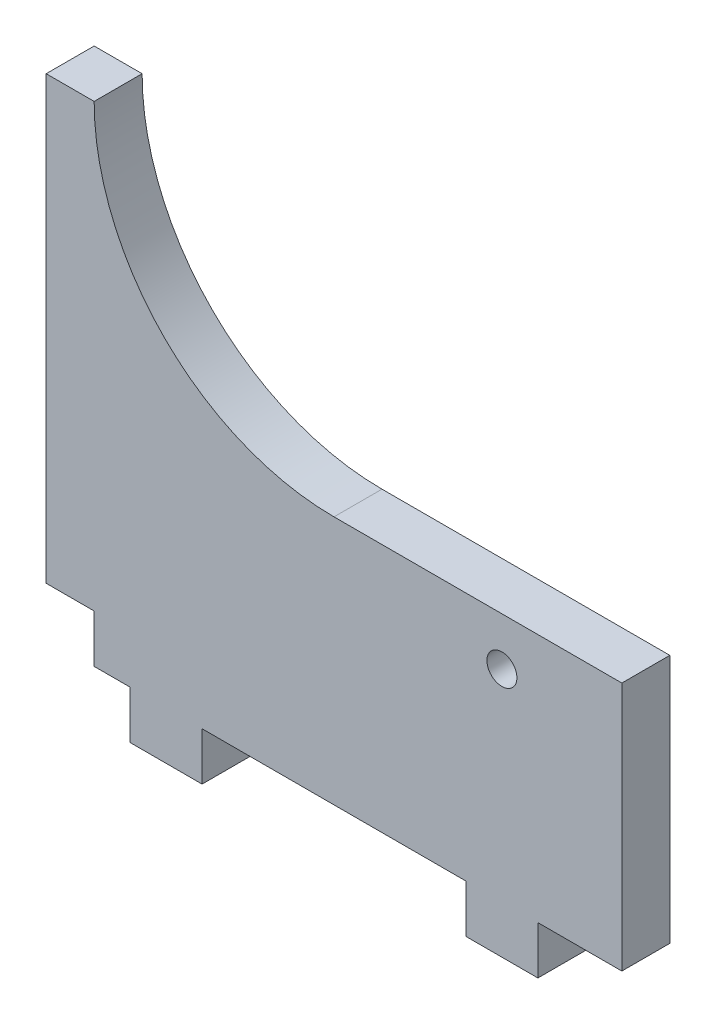
SolidWorks part; units mm, degrees
material "Acrylic (Medium-high impact)"
ref_plane "Front Plane" through (0, 0, 0) normal (0, 0, 1) x (1, 0, 0)
ref_plane "Top Plane" through (0, 0, 0) normal (0, 1, 0) x (1, 0, 0)
ref_plane "Right Plane" through (0, 0, 0) normal (1, 0, 0) x (0, 0, -1)
sketch "Sketch1" plane through (0, 0, 0) normal (0, 0, 1) x (1, 0, 0)
  line L0 (-76.2, 12.7) -> (-53.975, 12.7)
  line L1 (-53.975, 0) -> (-34.925, 0)
  line L2 (-76.2, 12.7) -> (-76.2, 142.24)
  line L3 (63.5, 142.24) -> (76.2, 142.24)
  line L4 (76.2, 12.7) -> (76.2, 142.24)
  line L5 (-34.925, 0) -> (-34.925, 12.7) construction
  line L6 (-53.975, 0) -> (-53.975, 12.7) construction
  line L7 (-34.925, 0) -> (-34.925, 12.7)
  line L8 (-53.975, 0) -> (-53.975, 12.7)
  line L9 (53.975, 0) -> (53.975, 12.7) construction
  line L10 (34.925, 0) -> (34.925, 12.7) construction
  line L11 (53.975, 0) -> (53.975, 12.7)
  line L12 (34.925, 0) -> (34.925, 12.7)
  line L13 (34.925, 0) -> (53.975, 0)
  line L14 (53.975, 12.7) -> (76.2, 12.7)
  line L15 (-34.925, 12.7) -> (34.925, 12.7)
  line L16 (-76.2, 142.24) -> (-63.5, 142.24)
  arc A0 (-63.5, 142.24) -> (63.5, 142.24) centre (0, 142.24) ccw
  dimension "D2" = 127
  dimension "D1" = 129.54
extrude "Extrude1" add sketch "Sketch1" along normal blind 12.7
sketch "Sketch2" plane through (0, 0, 12.7) normal (0, 0, 1) x (1, 0, 0)
  circle A0 centre (44.45, 66.04) radius 3.9687
  arc A1 (-63.5, 142.24) -> (63.5, 142.24) centre (0, 142.24) ccw construction
  dimension "D1" = 44.45
  dimension "D2" = 76.2
  dimension "D3" = 7.9375
extrude "Cut-Extrude1" cut sketch "Sketch2" against normal through all
sketch "Sketch3" plane through (0, 0, 12.7) normal (0, 0, 1) x (1, 0, 0)
  line L1 (-76.2, 12.7) -> (-63.5, 12.7)
  line L2 (-76.2, 12.7) -> (-76.2, 25.4)
  line L3 (-76.2, 25.4) -> (-63.5, 25.4)
  line L4 (-63.5, 12.7) -> (-63.5, 25.4)
  dimension "D1" = 12.7
extrude "Extrude2" cut sketch "Sketch3" against normal through all
sketch "Sketch4" plane through (0, 0, 12.7) normal (0, 0, 1) x (1, 0, 0)
  line L1 (0, 78.74) -> (105.9831, 78.74)
  line L2 (0, 78.74) -> (0, 153.9423)
  line L3 (0, 153.9423) -> (105.9831, 153.9423)
  line L4 (105.9831, 78.74) -> (105.9831, 153.9423)
  arc A0 (-63.5, 142.24) -> (63.5, 142.24) centre (0, 142.24) ccw construction
extrude "Extrude3" cut sketch "Sketch4" against normal through all
